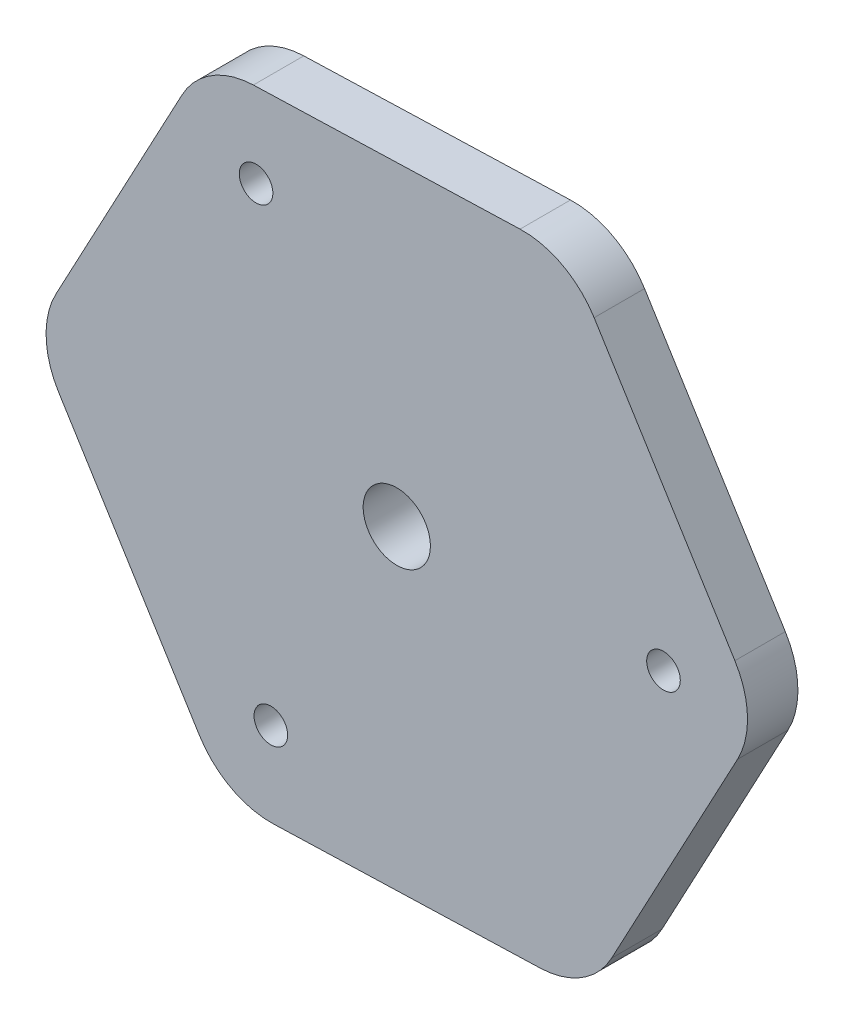
SolidWorks part; units mm, degrees
ref_plane "Front Plane" through (0, 0, 0) normal (0, 0, 1) x (1, 0, 0)
ref_plane "Top Plane" through (0, 0, 0) normal (0, 1, 0) x (1, 0, 0)
ref_plane "Right Plane" through (0, 0, 0) normal (1, 0, 0) x (0, 0, -1)
sketch "Sketch1" plane through (0, 0, 0) normal (0, 0, 1) x (1, 0, 0)
  line L6 (-52.9798, 153.114) -> (-36.2308, 126.1362)
  line L7 (-35.9108, 116.1413) -> (-50.8998, 88.1473)
  line L8 (-59.3957, 82.8728) -> (-91.1337, 81.8567)
  line L9 (-99.9495, 86.577) -> (-116.6985, 113.5548)
  line L10 (-117.0184, 123.5497) -> (-102.0294, 151.5437)
  line L11 (-93.5336, 156.8182) -> (-61.7956, 157.8343)
  circle A10 centre (-91.4537, 91.8515) radius 2
  circle A11 centre (-44.7266, 120.8616) radius 2
  circle A12 centre (-76.4646, 119.8455) radius 4
  circle A13 centre (-93.2136, 146.8234) radius 2
  arc A14 (-52.9798, 153.114) -> (-61.7956, 157.8343) centre (-61.4756, 147.8395) ccw
  arc A15 (-35.9108, 116.1413) -> (-36.2308, 126.1362) centre (-44.7266, 120.8616) ccw
  arc A16 (-59.3957, 82.8728) -> (-50.8998, 88.1473) centre (-59.7157, 92.8676) ccw
  arc A17 (-99.9495, 86.577) -> (-91.1337, 81.8567) centre (-91.4537, 91.8515) ccw
  arc A18 (-117.0184, 123.5497) -> (-116.6985, 113.5548) centre (-108.2026, 118.8294) ccw
  arc A19 (-93.5336, 156.8182) -> (-102.0294, 151.5437) centre (-93.2136, 146.8234) ccw
  point P1 (0, 0)
  dimension "D5" = 4
  dimension "D6" = 10
  dimension "D13" = 8
  dimension "D1" = 82.8728
  dimension "D2" = 59.3957
  dimension "D3" = 84.7309
  dimension "D4" = 31.7543
  dimension "D7" = 60
  dimension "D8" = 60
  dimension "D9" = 60
  dimension "D10" = 60
  dimension "D11" = 60
  dimension "D12" = 60
  dimension "D14" = 10
  dimension "D15" = 55
  dimension "D16" = 55
  dimension "D17" = 31.7543
  dimension "D18" = 31.7543
extrude "Boss-Extrude1" add sketch "Sketch1" along normal blind 6 separate body
